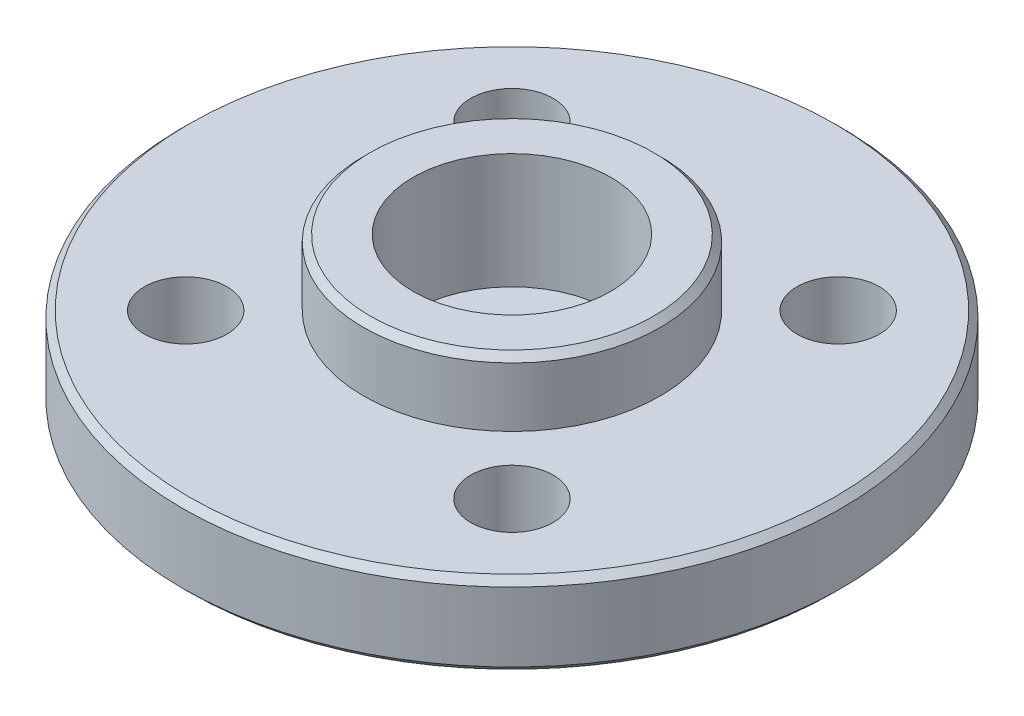
SolidWorks part; units mm, degrees
ref_plane "前视基准面" through (0, 0, 0) normal (0, 0, 1) x (1, 0, 0)
ref_plane "上视基准面" through (0, 0, 0) normal (0, 1, 0) x (1, 0, 0)
ref_plane "右视基准面" through (0, 0, 0) normal (1, 0, 0) x (0, 0, -1)
other "Configuration Table"
sketch "草图1" plane through (0, 0, 0) normal (0, 1, 0) x (1, 0, 0)
  circle A0 centre (0, 0) radius 10
extrude "凸台-拉伸1" add sketch "草图1" along normal mid plane 2.5
sketch "草图2" plane through (0, 1.25, 0) normal (0, 1, 0) x (1, 0, 0)
  circle A1 centre (4.9497, 4.9497) radius 1.25
  circle A2 centre (4.9497, -4.9497) radius 1.25
  circle A3 centre (-4.9497, 4.9497) radius 1.25
  circle A4 centre (-4.9497, -4.9497) radius 1.25
  point P0 (0, 0)
  dimension "D1" = 7
extrude "切除-拉伸1" cut sketch "草图2" against normal through all contours A3 | A4 | A2 | A1
sketch "草图3" plane through (0, 1.25, 0) normal (0, 1, 0) x (1, 0, 0)
  circle A0 centre (0, 0) radius 4.5
extrude "凸台-拉伸2" add sketch "草图3" along normal blind 2 contours A0
sketch "草图4" plane through (0, 3.25, 0) normal (0, 1, 0) x (1, 0, 0)
  circle A0 centre (0, 0) radius 3
extrude "切除-拉伸2" cut sketch "草图4" against normal blind 3.5
sketch "草图5" plane through (0, -1.25, 0) normal (0, -1, 0) x (1, 0, 0)
  circle A0 centre (0, 0) radius 1.5
  point P3 (0, 0)
extrude "切除-拉伸3" cut sketch "草图5" against normal blind 1
chamfer "倒角1" distance 0.2 angle 45 1 edges at (0, 3.25, 4.5)
chamfer "倒角2" distance 0.2 angle 45 2 edges at (0, -1.25, 10) (0, 1.25, 10)
chamfer "倒角3" distance 0.2 angle 45 1 edges at (0, -1.25, -1.5)
